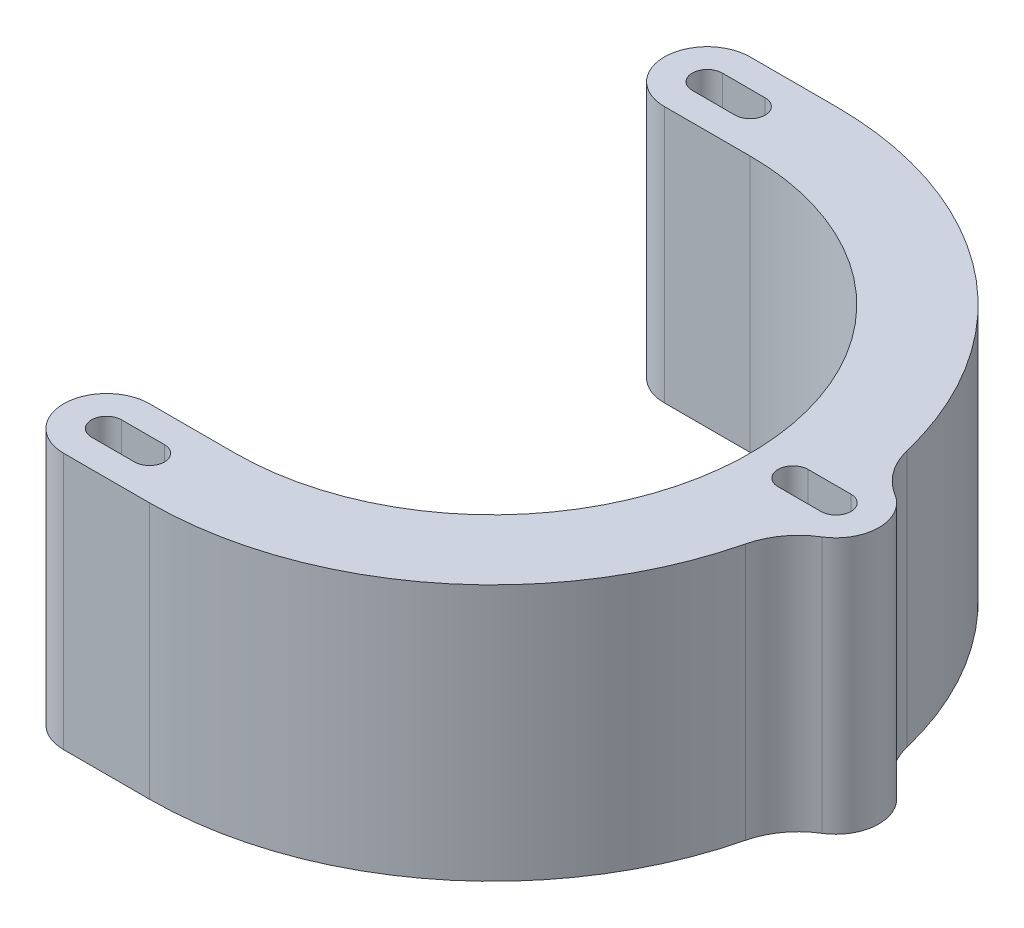
SolidWorks part; units mm, degrees
ref_plane "Plan de face" through (0, 0, 0) normal (0, 0, 1) x (1, 0, 0)
ref_plane "Plan de dessus" through (0, 0, 0) normal (0, 1, 0) x (1, 0, 0)
ref_plane "Plan de droite" through (0, 0, 0) normal (1, 0, 0) x (0, 0, -1)
sketch "Esquisse1" plane through (0, 0, 0) normal (0, 1, 0) x (1, 0, 0)
  line L0 (0, 42) -> (-12, 42) construction
  line L1 (0, -42) -> (-12, -42) construction
  line L2 (42, 0) -> (48, 0) construction
  line L3 (-12, 48) -> (0, 48)
  line L4 (-12, 36) -> (0, 36)
  line L5 (-12, -36) -> (0, -36)
  line L6 (-12, -48) -> (0, -48)
  line L7 (-12, 42) -> (-6, 42) construction
  line L8 (-12, 44.1) -> (-6, 44.1)
  line L9 (-12, 39.9) -> (-6, 39.9)
  line L10 (48, 0) -> (42, 0) construction
  line L11 (48, -2.1) -> (42, -2.1)
  line L12 (48, 2.1) -> (42, 2.1)
  line L13 (-12, -42) -> (-6, -42) construction
  line L14 (-12, -39.9) -> (-6, -39.9)
  line L15 (-12, -44.1) -> (-6, -44.1)
  arc A0 (0, -36) -> (0, 36) centre (0, 0) ccw
  circle A1 centre (0, 0) radius 42 construction
  arc A2 (0, -48) -> (46.6552, -11.2825) centre (0, 0) ccw
  arc A3 (-12, 48) -> (-12, 36) centre (-12, 42) ccw
  arc A4 (-12, -36) -> (-12, -48) centre (-12, -42) ccw
  arc A5 (51.1406, -5.1124) -> (51.1406, 5.1124) centre (48, 0) ccw
  arc A6 (46.6552, -11.2825) -> (51.1406, -5.1124) centre (56.375, -13.633) cw
  circle A7 centre (0, 0) radius 48 construction
  arc A8 (51.1406, 5.1124) -> (46.6552, 11.2825) centre (56.375, 13.633) cw
  arc A9 (46.6552, 11.2825) -> (0, 48) centre (0, 0) ccw
  arc A10 (-12, 44.1) -> (-12, 39.9) centre (-12, 42) ccw
  circle A11 centre (0, 0) radius 36 construction
  arc A12 (-6, 39.9) -> (-6, 44.1) centre (-6, 42) ccw
  arc A13 (48, -2.1) -> (48, 2.1) centre (48, 0) ccw
  arc A14 (42, 2.1) -> (42, -2.1) centre (42, 0) ccw
  arc A15 (-12, -39.9) -> (-12, -44.1) centre (-12, -42) ccw
  arc A16 (-6, -44.1) -> (-6, -39.9) centre (-6, -42) ccw
  point P23 (46, 0)
  point P26 (-9, 42)
  point P27 (47.625, 5.9883)
  point P29 (34.427, 10.5254)
  point P35 (45, 0)
  point P40 (-9, -42)
  dimension "D1" = 6
  dimension "D2" = 84
  dimension "D4" = 12
  dimension "D5" = 6
  dimension "D7" = 10
  dimension "D10" = 2.1
  dimension "D11" = 2.1
  dimension "D13" = 2.1
  dimension "D6" = 12
  dimension "D8" = 12
  dimension "D9" = 6
  dimension "D12" = 6
  dimension "D3" = 12
extrude "Boss.-Extru.1" add sketch "Esquisse1" along normal blind 35.9
sketch "Esquisse2" plane through (0, 0, 0) normal (0, 1, 0) x (1, 0, 0)
  line L0 (0, 0) -> (29.6985, 29.6985) construction
  line L1 (0, 0) -> (36, 0) construction
  line L2 (0, 0) -> (29.6985, -29.6985) construction
  circle A0 centre (29.6985, 29.6985) radius 1.25
  arc A1 (0, -36) -> (0, 36) centre (0, 0) ccw construction
  circle A2 centre (29.6985, -29.6985) radius 1.25
  dimension "D2" = 2.5
  dimension "D1" = 45
  dimension "D3" = 42
extrude "Enlèv. mat.-Extru.1" cut sketch "Esquisse2" along normal blind 10
sketch "Esquisse3" [suppressed] plane through (0, 0, 0) normal (0, 1, 0) x (1, 0, 0)
  line L0 (-12, 36) -> (0, 36) construction
  line L1 (0, 48) -> (-12, 48) construction
  line L2 (-12, 36) -> (-6, 36)
  line L3 (-6, 48) -> (-12, 48)
  arc A0 (-12, 48) -> (-12, 36) centre (-12, 42) ccw construction
  arc A1 (-12, 48) -> (-12, 36) centre (-12, 42) ccw
  arc A2 (-6, 36) -> (-6, 48) centre (-6, 42) ccw
extrude "Enlèv. mat.-Extru.2" [suppressed] cut sketch "Esquisse3" along normal through all flip side to cut
